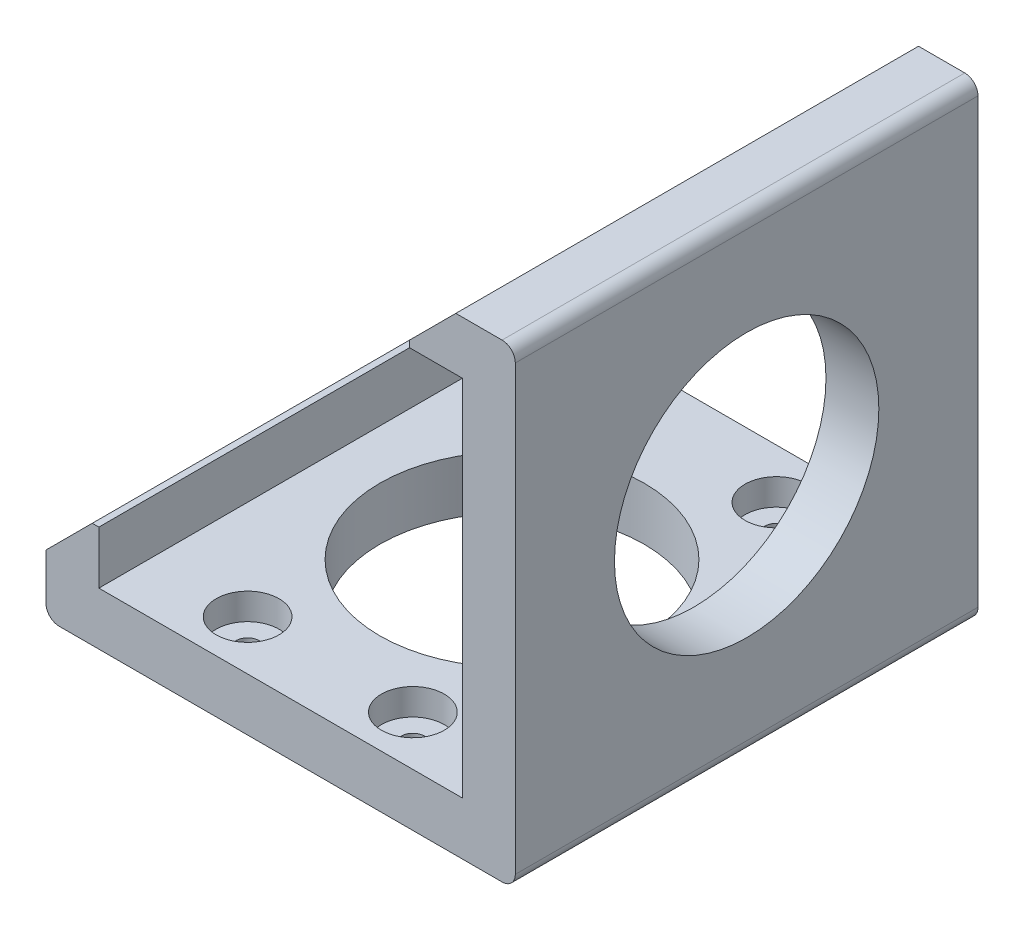
SolidWorks part; units mm, degrees
ref_plane "Front Plane" through (0, 0, 0) normal (0, 0, 1) x (1, 0, 0)
ref_plane "Top Plane" through (0, 0, 0) normal (0, 1, 0) x (1, 0, 0)
ref_plane "Right Plane" through (0, 0, 0) normal (1, 0, 0) x (0, 0, -1)
sketch "Sketch1" plane through (0, 0, 0) normal (0, 0, 1) x (1, 0, 0)
  line L0 (-55, 0) -> (0, 0)
  line L1 (0, 0) -> (0, 55)
  line L2 (0, 55) -> (-8, 55)
  line L9 (-55, 8) -> (-55, 0)
  line L10 (-63, 8) -> (-63, -8)
  line L11 (-63, -8) -> (8, -8)
  line L12 (8, -8) -> (8, 63)
  line L13 (8, 63) -> (-8, 63)
  line L14 (-8, 63) -> (-8, 55)
  line L15 (-63, 8) -> (-55, 8)
  dimension "D1" = 55
  dimension "D2" = 55
  dimension "D4" = 8
  dimension "D5" = 8
  dimension "D3" = 8
extrude "Boss-Extrude1" add sketch "Sketch1" along normal blind 70
chamfer "Chamfer1" distance 7 angle 45 2 edges at (-8, 63, 35) (-63, 8, 35)
fillet "Fillet1" radius 2 3 edges at (8, 63, 35) (8, -8, 35) (-63, -8, 35)
sketch "Sketch2" plane through (0, -8, 0) normal (0, -1, 0) x (1, 0, 0)
  line L0 (6, 0) -> (-61, 70) construction
  line L2 (-40, 7.5) -> (-15, 7.5) construction
  line L3 (-40, 7.5) -> (-40, 62.5) construction
  line L4 (-40, 62.5) -> (-15, 62.5) construction
  line L5 (-15, 7.5) -> (-15, 62.5) construction
  line L6 (-40, 7.5) -> (-15, 62.5) construction
  line L7 (-40, 62.5) -> (-15, 7.5) construction
  circle A0 centre (-40, 62.5) radius 1.75
  circle A1 centre (-15, 62.5) radius 1.75
  circle A2 centre (-15, 7.5) radius 1.75
  circle A3 centre (-40, 7.5) radius 1.75
  circle A4 centre (-27.5, 35) radius 20
  point P4 (-27.5, 35)
  dimension "D3" = 3.5
  dimension "D4" = 40
  dimension "D1" = 55
  dimension "D2" = 25
extrude "Cut-Extrude1" cut sketch "Sketch2" against normal blind 23
sketch "Sketch3" plane through (0, 0, 0) normal (0, 1, 0) x (1, 0, 0)
  circle A0 centre (-40, -62.5) radius 1.75 construction
  circle A1 centre (-15, -62.5) radius 1.75 construction
  circle A2 centre (-15, -7.5) radius 1.75 construction
  circle A3 centre (-40, -7.5) radius 1.75 construction
  circle A24 centre (-40, -62.5) radius 1.75
  circle A25 centre (-15, -62.5) radius 1.75
  circle A26 centre (-15, -7.5) radius 1.75
  circle A27 centre (-40, -7.5) radius 1.75
  circle A28 centre (-40, -62.5) radius 4.75
  circle A29 centre (-15, -62.5) radius 4.75
  circle A30 centre (-15, -7.5) radius 4.75
  circle A31 centre (-40, -7.5) radius 4.75
  dimension "D1" = 3
extrude "Cut-Extrude2" cut sketch "Sketch3" against normal blind 4
sketch "Sketch5" plane through (8, 0, 0) normal (1, 0, 0) x (0, 0, -1)
  line L0 (-70, 61) -> (0, -6) construction
  circle A0 centre (-35, 27.5) radius 20
  dimension "D1" = 40
extrude "Cut-Extrude3" cut sketch "Sketch5" against normal blind 23
